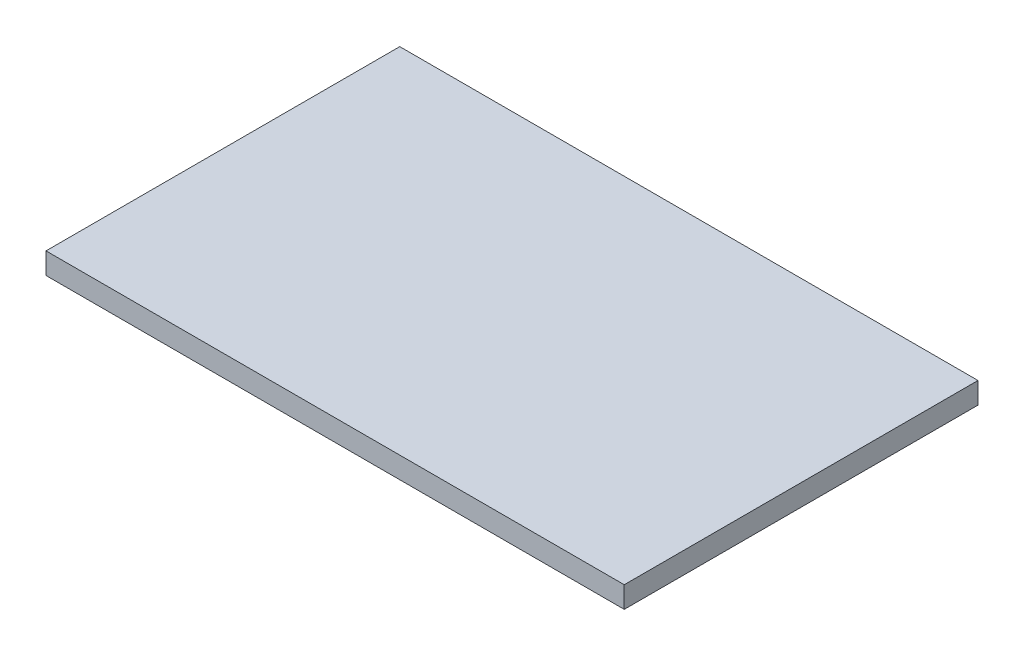
SolidWorks part; units mm, degrees
ref_plane "Front Plane" through (0, 0, 0) normal (0, 0, 1) x (1, 0, 0)
ref_plane "Top Plane" through (0, 0, 0) normal (0, 1, 0) x (1, 0, 0)
ref_plane "Right Plane" through (0, 0, 0) normal (1, 0, 0) x (0, 0, -1)
sketch "Sketch1" plane through (0, 0, 0) normal (0, 1, 0) x (1, 0, 0)
  line L1 (160.8869, 98.425) -> (-160.8869, 98.425)
  line L2 (160.8869, 98.425) -> (160.8869, -98.425)
  line L3 (160.8869, -98.425) -> (-160.8869, -98.425)
  line L4 (-160.8869, 98.425) -> (-160.8869, -98.425)
  line L5 (0, -98.425) -> (0, 98.425) construction
  line L6 (160.8869, 0) -> (-160.8869, 0) construction
  point P0 (0, 0)
  dimension "D1" = 321.7738
  dimension "D2" = 196.85
extrude "Boss-Extrude1" add sketch "Sketch1" along normal blind 11.8872
